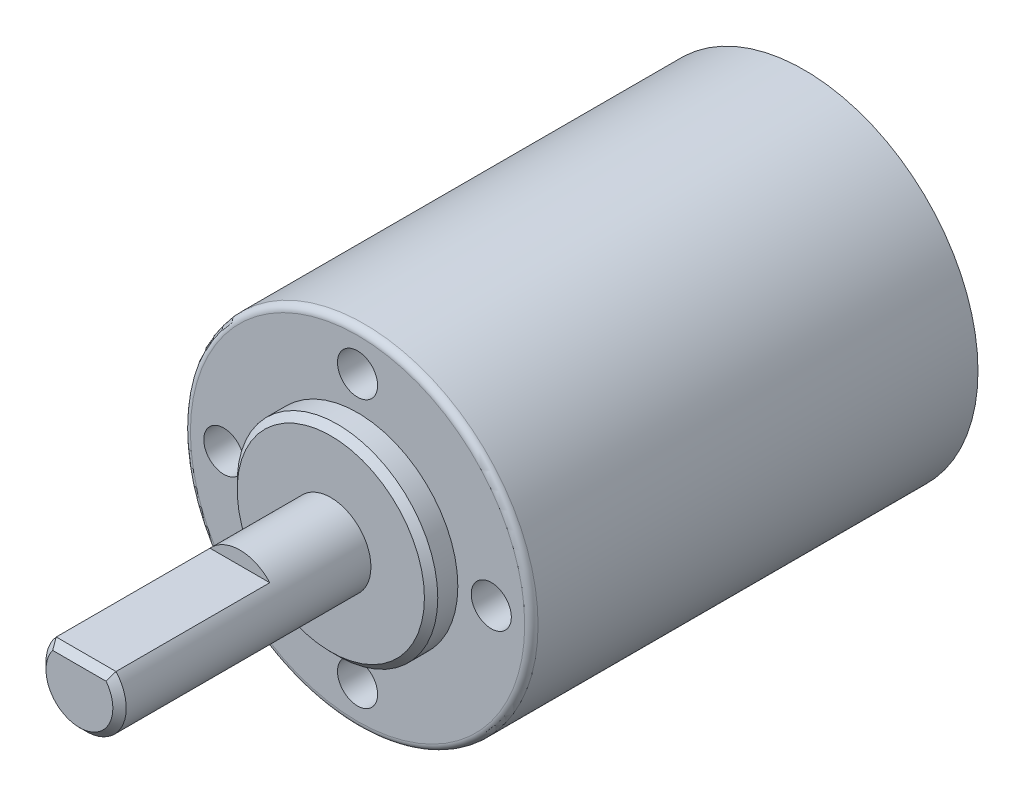
SolidWorks part; units mm, degrees
ref_plane "Plan de face" through (0, 0, 0) normal (0, 0, 1) x (1, 0, 0)
ref_plane "Plan de dessus" through (0, 0, 0) normal (0, 1, 0) x (1, 0, 0)
ref_plane "Plan de droite" through (0, 0, 0) normal (1, 0, 0) x (0, 0, -1)
sketch "Esquisse1" plane through (0, 0, 0) normal (0, 0, 1) x (1, 0, 0)
  circle A0 centre (0, 0) radius 13
  dimension "D1" = 26
extrude "Boss.-Extru.1" add sketch "Esquisse1" along normal blind 33.4
sketch "Esquisse2" plane through (0, 0, 33.4) normal (0, 0, 1) x (1, 0, 0)
  circle A0 centre (0, 0) radius 7.5
  dimension "D1" = 15
extrude "Boss.-Extru.2" add sketch "Esquisse2" along normal blind 2
sketch "Esquisse3" plane through (0, 0, 35.4) normal (0, 0, 1) x (1, 0, 0)
  circle A0 centre (0, 0) radius 3
  dimension "D1" = 6
extrude "Boss.-Extru.3" add sketch "Esquisse3" along normal blind 18.8
sketch "Esquisse4" plane through (0, 0, 54.2) normal (0, 0, 1) x (1, 0, 0)
  line L0 (-2.2361, 2) -> (2.2361, 2)
  arc A0 (-2.2361, 2) -> (2.2361, 2) centre (0, 0) cw
  circle A1 centre (0, 0) radius 3 construction
  circle A2 centre (0, 0) radius 3 construction
  dimension "D1" = 2
extrude "Enlèv. mat.-Extru.1" cut sketch "Esquisse4" against normal blind 12
chamfer "Chanfrein1" distance 0.5 angle 45 3 edges at (7.5, 0, 35.4) (0, -3, 54.2) (0, 2, 54.2)
sketch "Esquisse5" plane through (0, 0, 33.4) normal (0, 0, 1) x (1, 0, 0)
  line L0 (0, 13) -> (0, -13) construction
  circle A0 centre (0, 0) radius 13 construction
  circle A1 centre (0, 10) radius 1.5
  circle A2 centre (10, 0) radius 1.5
  circle A3 centre (0, -10) radius 1.5
  circle A4 centre (-10, 0) radius 1.5
  dimension "D1" = 3
  dimension "D2" = 10
  dimension "D3" = 4
extrude "Enlèv. mat.-Extru.2" cut sketch "Esquisse5" against normal blind 5
fillet "Congé1" radius 0.5 1 edges at (13, 0, 33.4)
